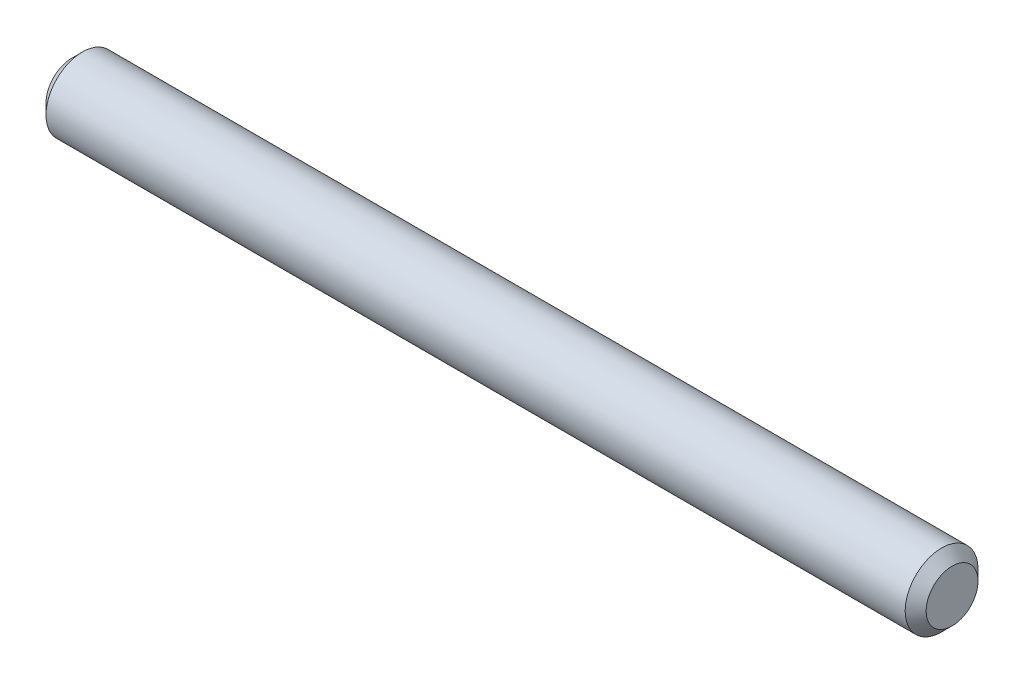
SolidWorks part; units mm, degrees
ref_plane "Front Plane" through (0, 0, 0) normal (0, 0, 1) x (1, 0, 0)
ref_plane "Top Plane" through (0, 0, 0) normal (0, 1, 0) x (1, 0, 0)
ref_plane "Right Plane" through (0, 0, 0) normal (1, 0, 0) x (0, 0, -1)
sketch "Sketch1" plane through (0, 0, 0) normal (1, 0, 0) x (0, 0, -1)
  circle A0 centre (0, 0) radius 3.475
  dimension "D1" = 6.95
extrude "Boss-Extrude1" add sketch "Sketch1" along normal mid plane 84
chamfer "Chamfer1" distance 1 angle 45 2 edges at (42, 0, -3.475) (-42, 0, -3.475)
